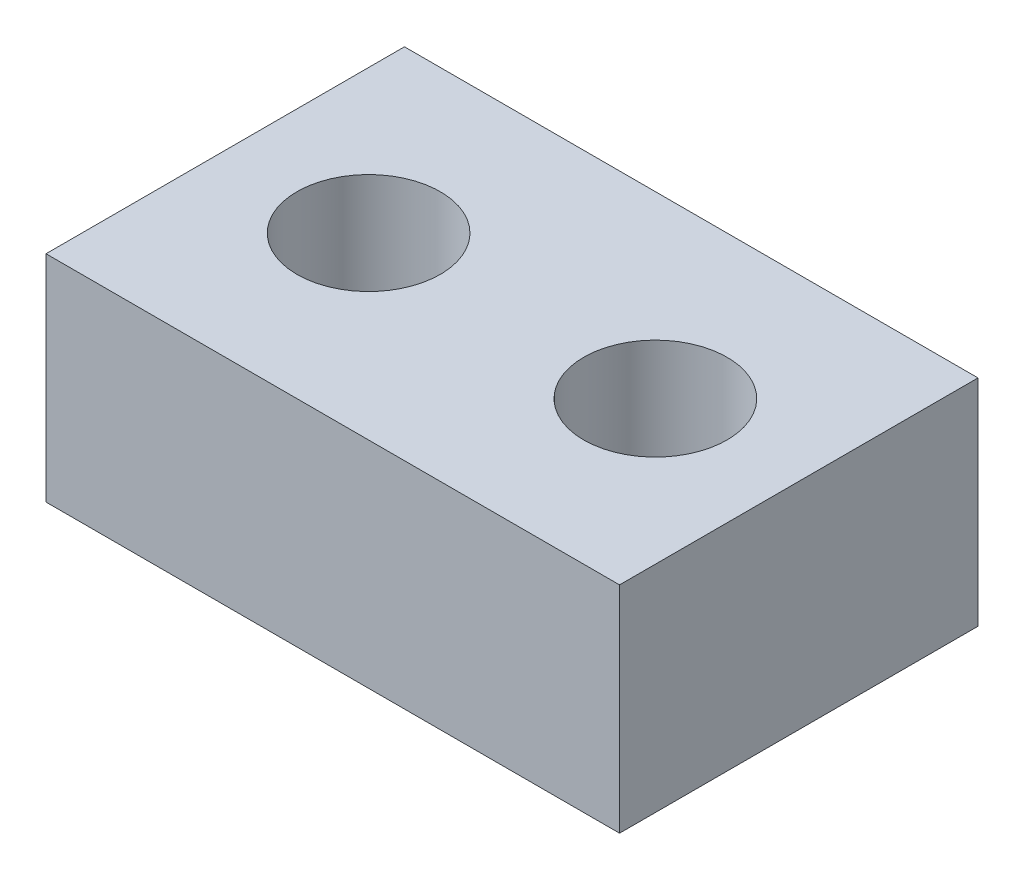
SolidWorks part; units mm, degrees
ref_plane "정면" through (0, 0, 0) normal (0, 0, 1) x (1, 0, 0)
ref_plane "윗면" through (0, 0, 0) normal (0, 1, 0) x (1, 0, 0)
ref_plane "우측면" through (0, 0, 0) normal (1, 0, 0) x (0, 0, -1)
sketch "스케치1" plane through (0, 0, 0) normal (0, 1, 0) x (1, 0, 0)
  line L1 (-55.4121, -28.1858) -> (24.5879, -28.1858)
  line L2 (-55.4121, -28.1858) -> (-55.4121, 21.8142)
  line L3 (-55.4121, 21.8142) -> (24.5879, 21.8142)
  line L4 (24.5879, -28.1858) -> (24.5879, 21.8142)
  circle A0 centre (-35.4121, -3.1858) radius 10
  circle A1 centre (4.5879, -3.1858) radius 10
  point P8 (0, 0)
  point P11 (-33.0755, -1.3124)
  dimension "D1" = 80
  dimension "D3" = 20
  dimension "D2" = 50
  dimension "D4" = 20
  dimension "D5" = 20
  dimension "D6" = 40
  dimension "D7" = 25
extrude "보스-돌출1" add sketch "스케치1" along normal blind 30
